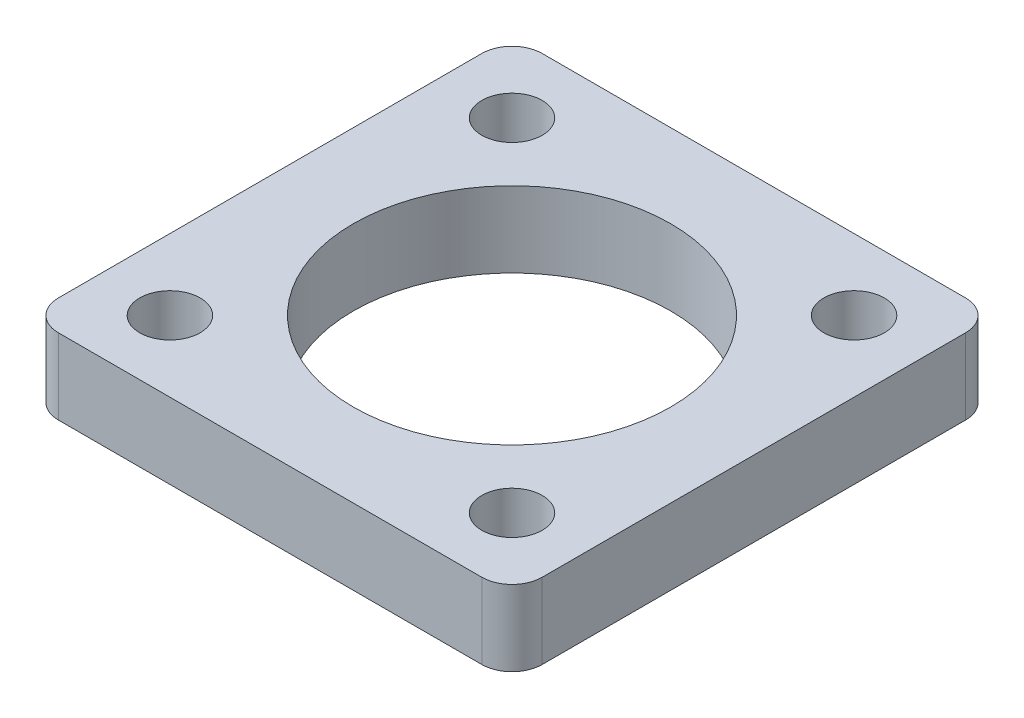
SolidWorks part; units mm, degrees
ref_plane "Front Plane" through (0, 0, 0) normal (0, 0, 1) x (1, 0, 0)
ref_plane "Top Plane" through (0, 0, 0) normal (0, 1, 0) x (1, 0, 0)
ref_plane "Right Plane" through (0, 0, 0) normal (1, 0, 0) x (0, 0, -1)
sketch "Sketch1" plane through (0, 0, 0) normal (0, 1, 0) x (1, 0, 0)
  line L0 (-16, 16) -> (16, 16)
  line L6 (-16, 16) -> (-16, -16)
  line L7 (-16, -16) -> (16, -16)
  line L8 (16, 16) -> (16, -16)
  line L9 (-16, 16) -> (16, -16) construction
  circle A1 centre (0, 0) radius 10.5
  circle A2 centre (-11.3137, 11.3137) radius 2
  circle A3 centre (11.3137, 11.3137) radius 2
  circle A4 centre (11.3137, -11.3137) radius 2
  circle A5 centre (-11.3137, -11.3137) radius 2
  circle A6 centre (0, 0) radius 16 construction
  point P20 (0, 0)
  dimension "D2" = 21
  dimension "D3" = 32
  dimension "D1" = 4
  dimension "D4" = 32
  dimension "D5" = 4
extrude "Boss-Extrude1" add sketch "Sketch1" along normal blind 5
fillet "Fillet1" radius 2 4 edges at (16, 2.5, 16) (-16, 2.5, -16) (16, 2.5, -16) (-16, 2.5, 16)
